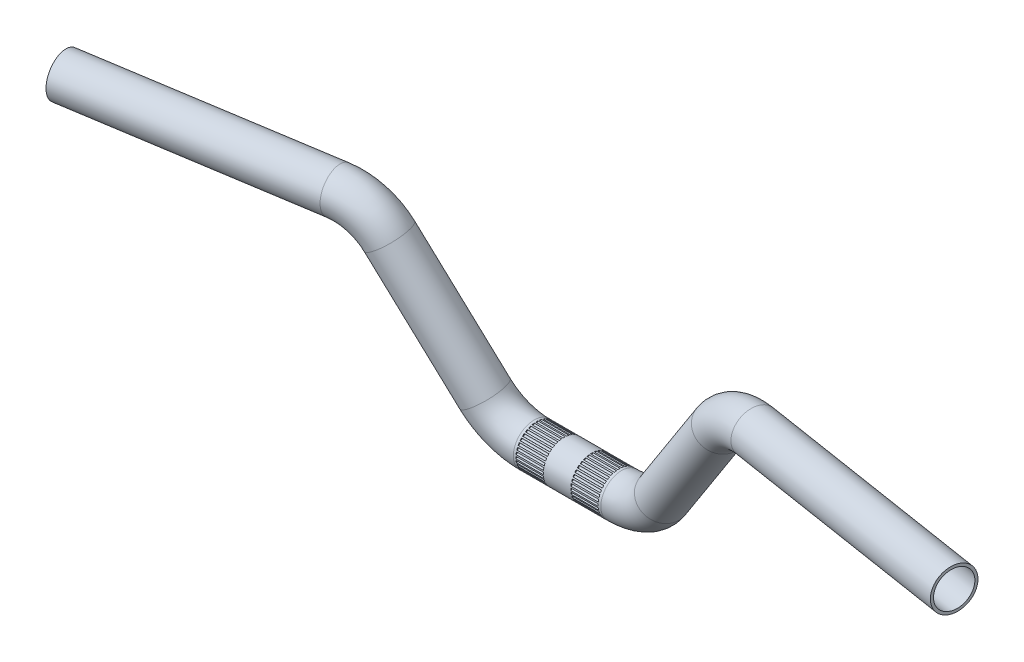
SolidWorks part; units mm, degrees
ref_plane "Front Plane" through (0, 0, 0) normal (0, 0, 1) x (1, 0, 0)
ref_plane "Top Plane" through (0, 0, 0) normal (0, 1, 0) x (1, 0, 0)
ref_plane "Right Plane" through (0, 0, 0) normal (1, 0, 0) x (0, 0, -1)
ref_plane "Plane1" through (0, 0, 25) normal (0, 0, 1) x (1, 0, 0)
ref_plane "Plane2" through (0, 0, 63) normal (0, 0, 1) x (1, 0, 0)
sketch "Sketch1" plane through (0, 0, 25) normal (0, 0, 1) x (1, 0, 0)
  point P0 (165, 140)
  dimension "D1" = 140
  dimension "D2" = 165
sketch "Sketch2" plane through (0, 0, 63) normal (0, 0, 1) x (1, 0, 0)
  point P0 (406, 140)
  dimension "D1" = 140
  dimension "D2" = 406
sketch3d "3DSketch1"
  line L0 (0, 0, 0) -> (39.8845, 0, 0)
  line L1 (80.9205, 21.0998, 3.7678) -> (150.4234, 119.3866, 21.319)
  line L2 (190.2022, 140, 28.9738) -> (406, 140, 63)
  arc A0 (39.8845, 0, 0) -> (80.9205, 21.0998, 3.7678) centre (39.8845, 49.2214, 8.7895) ccw
  arc A1 (150.4234, 119.3866, 21.319) -> (190.2022, 140, 28.9738) centre (190.717, 90.1094, 25.7087) ccw
  point P9 (66, 0, 0)
  point P10 (39.8845, 40.4318, 58.0109)
  point P13 (165, 140, 25)
  point P14 (198.4876, 93.4148, -23.5731)
  dimension "D1" = 50
  dimension "D2" = 66
sketch "Sketch3" plane through (0, 0, 0) normal (1, 0, 0) x (0, 0, -1)
  circle A0 centre (0, 0) radius 19
  dimension "D1" = 38
sweep "Sweep-Thin1" add profiles "Sketch3" path "3DSketch1" parameters "D1"=2.5
mirror "Mirror1" about plane through (0, 0, 0) normal (1, 0, 0) of "Sweep-Thin1"
sketch "Sketch4" plane through (0, 0, 0) normal (1, 0, 0) x (0, 0, -1)
  line L0 (0, 0) -> (0, -19) construction
  circle A0 centre (0, 0) radius 19 construction
  circle A1 centre (0, -19) radius 1
  dimension "D1" = 2
  dimension "D2" = 19
extrude "Cut-Extrude3" cut sketch "Sketch4" against normal blind 25 from offset 12.5 offset against normal yes
pattern_circular "CirPattern2" count 36 over 360 about axis through (0, 0, 0) along (1, 0, 0) of "Cut-Extrude3"
mirror "Mirror3" about plane through (0, 0, 0) normal (1, 0, 0) of "CirPattern2", "Cut-Extrude3"
